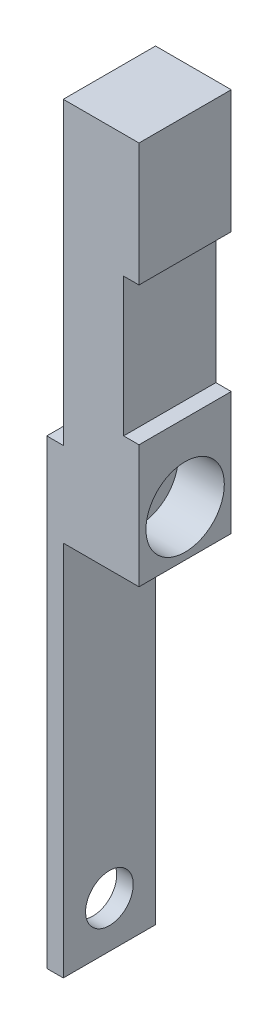
SolidWorks part; units mm, degrees
ref_plane "Plan de face" through (0, 0, 0) normal (0, 0, 1) x (1, 0, 0)
ref_plane "Plan de dessus" through (0, 0, 0) normal (0, 1, 0) x (1, 0, 0)
ref_plane "Plan de droite" through (0, 0, 0) normal (1, 0, 0) x (0, 0, -1)
sketch "Esquisse1" plane through (0, 0, 0) normal (0, 0, 1) x (1, 0, 0)
  line L0 (6.25, -27.5) -> (6.25, 27.5) construction
  line L1 (6.25, -15) -> (8.4, -15)
  line L2 (6.25, -15) -> (6.25, -75)
  line L3 (6.25, -75) -> (8.4, -75)
  line L4 (8.4, -26) -> (8.4, -75)
  line L5 (-6.25, -20) -> (6.25, -20) construction
  line L7 (8.4, -26) -> (18.25, -26)
  line L8 (8.4, -15) -> (8.4, 24)
  line L9 (8.4, 24) -> (18.25, 24)
  line L10 (18.25, -26) -> (18.25, 24)
  dimension "D1" = 2.15
  dimension "D2" = 5
  dimension "D3" = 60
  dimension "D4" = 6
  dimension "D5" = 50
  dimension "D6" = 2.15
  dimension "D7" = 12
extrude "Boss.-Extru.1" add sketch "Esquisse1" along normal mid plane 12
sketch "Esquisse2" plane through (18.25, 0, 0) normal (1, 0, 0) x (0, 0, -1)
  line L0 (0, 24) -> (0, -79.7243) construction
  line L1 (-6, 24) -> (6, 24) construction
  line L2 (-6, -26) -> (6, -26) construction
  circle A0 centre (0, -20) radius 5.1
  point P7 (0, -19.7249)
  dimension "D1" = 10.2
  dimension "D2" = 6
extrude "Enlèv. mat.-Extru.1" cut sketch "Esquisse2" against normal blind 6
sketch "Esquisse3" plane through (12.25, 0, 0) normal (1, 0, 0) x (0, 0, -1)
  circle A0 centre (0, -20) radius 3.1
  dimension "D1" = 6.2
extrude "Enlèv. mat.-Extru.2" cut sketch "Esquisse3" against normal through all
sketch "Esquisse4" plane through (8.4, 0, 0) normal (1, 0, 0) x (0, 0, -1)
  line L0 (0, -75) -> (0, -26) construction
  line L1 (-6, -75) -> (6, -75) construction
  line L2 (-6, -26) -> (6, -26) construction
  circle A0 centre (0, -69) radius 3.1
  dimension "D1" = 6.2
  dimension "D2" = 6
extrude "Enlèv. mat.-Extru.3" cut sketch "Esquisse4" against normal through all
sketch "Esquisse5" plane through (0, 0, 0) normal (0, 0, 1) x (1, 0, 0)
  line L0 (18.25, 24) -> (8.4, 24) construction
  line L1 (30.0459, 8) -> (16.25, 8)
  line L2 (30.0459, 8) -> (30.0459, -10)
  line L3 (30.0459, -10) -> (16.25, -10)
  line L4 (16.25, 8) -> (16.25, -10)
  line L6 (18.25, -26) -> (18.25, 24) construction
  dimension "D1" = 16
  dimension "D2" = 18
  dimension "D3" = 2
extrude "Enlèv. mat.-Extru.4" cut sketch "Esquisse5" against normal through all and the other way through all
